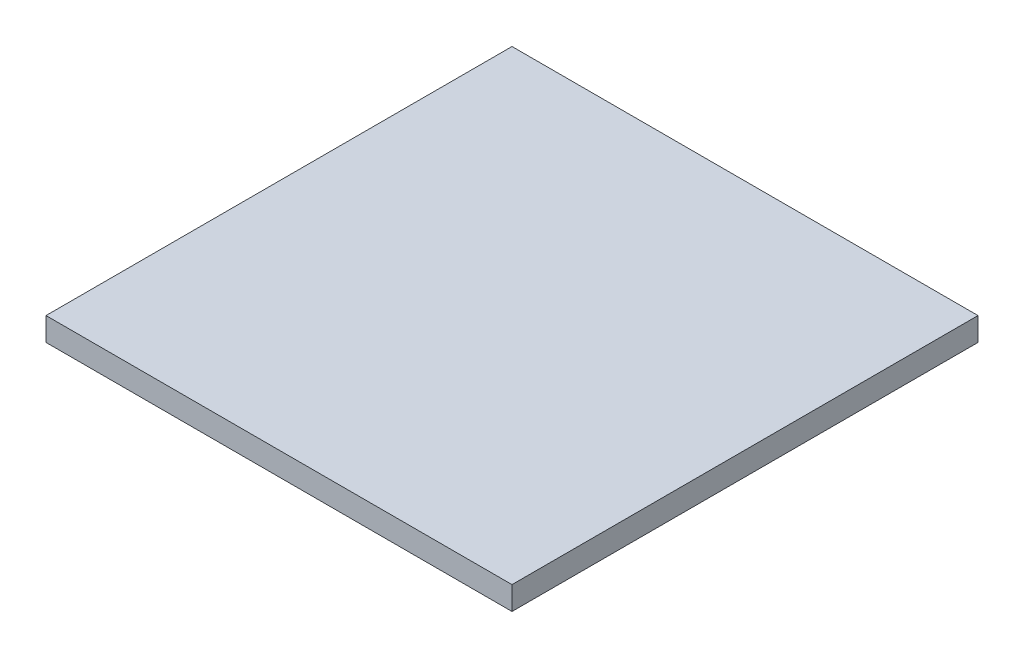
SolidWorks part; units mm, degrees
ref_plane "Alzado" through (0, 0, 0) normal (0, 0, 1) x (1, 0, 0)
ref_plane "Planta" through (0, 0, 0) normal (0, 1, 0) x (1, 0, 0)
ref_plane "Vista lateral" through (0, 0, 0) normal (1, 0, 0) x (0, 0, -1)
sketch "Croquis1" plane through (0, 0, 0) normal (0, 1, 0) x (1, 0, 0)
  line L1 (0, 0) -> (10, 0)
  line L2 (0, 0) -> (0, 10)
  line L3 (0, 10) -> (10, 10)
  line L4 (10, 0) -> (10, 10)
  dimension "D1" = 10
extrude "Saliente-Extruir1" add sketch "Croquis1" along normal blind 0.5
